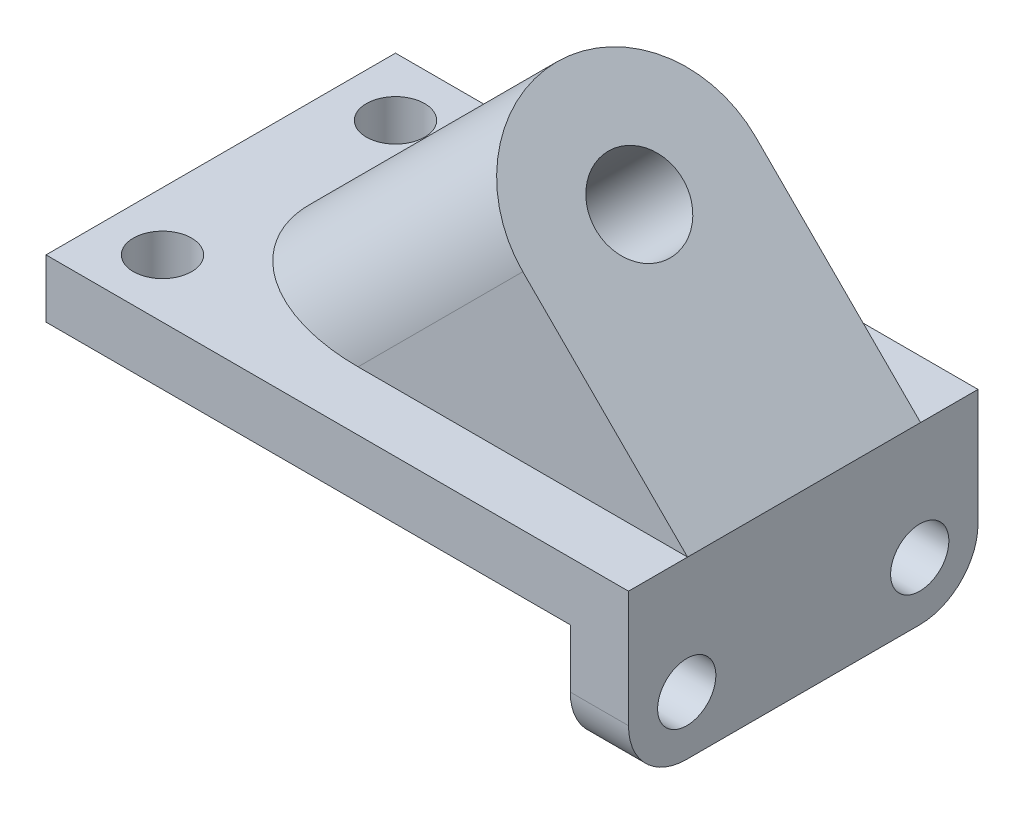
SolidWorks part; units mm, degrees
ref_plane "Front Plane" through (0, 0, 0) normal (0, 0, 1) x (1, 0, 0)
ref_plane "Top Plane" through (0, 0, 0) normal (0, 1, 0) x (1, 0, 0)
ref_plane "Right Plane" through (0, 0, 0) normal (1, 0, 0) x (0, 0, -1)
sketch "Sketch1" plane through (0, 0, 0) normal (0, 1, 0) x (1, 0, 0)
  line L0 (0, 0) -> (127, 0)
  line L1 (127, 0) -> (127, 76.2)
  line L2 (127, 76.2) -> (0, 76.2)
  line L3 (0, 76.2) -> (0, 0)
extrude "Boss-Extrude1" add sketch "Sketch1" along normal blind 12.7
sketch "Sketch2" plane through (0, 12.7, 0) normal (0, 1, 0) x (1, 0, 0)
  line L0 (0, 0) -> (127, 0) construction
  line L1 (127, 76.2) -> (114.3, 76.2)
  line L2 (127, 76.2) -> (127, 0)
  line L3 (127, 0) -> (114.3, 0)
  line L4 (114.3, 76.2) -> (114.3, 0)
extrude "Boss-Extrude2" add sketch "Sketch2" against normal blind 38.1
sketch "Sketch5" plane through (0, 12.7, 0) normal (0, 1, 0) x (1, 0, 0)
  circle A0 centre (12.7, 63.5) radius 6.35
  circle A1 centre (12.7, 12.7) radius 6.35
  dimension "D1" = 12.7
fillet "Fillet1" radius 12.7 1 edges at (120.65, -25.4, 0)
fillet "Fillet2" radius 12.7 1 edges at (120.65, -25.4, -76.2)
ref_plane "Plane1" through (69.85, 69.85, 0) normal (0.7071, 0.7071, 0) x (0, 0, -1)
sketch "Sketch7" plane through (69.85, 69.85, 0) normal (0.7071, 0.7071, 0) x (0, 0, -1)
  line L0 (63.6781, -80.8223) -> (12.8781, -80.8223)
  line L1 (0, -80.8223) -> (76.2, -80.8223) construction
  line L2 (12.8781, -80.8223) -> (12.8781, -30.0223)
  line L3 (63.6781, -80.8223) -> (63.6781, -30.0223)
  arc A0 (12.8781, -30.0223) -> (63.6781, -30.0223) centre (38.2781, -30.0223) cw
  circle A1 centre (38.2781, -30.0223) radius 9.525
  dimension "D4" = 19.05
  dimension "D1" = 50.8
  dimension "D2" = 50.8
  dimension "D3" = 12.5219
extrude "Boss-Extrude3" add sketch "Sketch7" against normal up to surface up to face at (63.5, 12.7, -38.1)
extrude "Cut-Extrude1" cut sketch "Sketch5" against normal blind 38.1
sketch "Sketch8" plane through (127, 0, 0) normal (1, 0, 0) x (0, 0, -1)
  circle A0 centre (12.7, -12.7) radius 6.35
  circle A1 centre (63.5, -12.7) radius 6.35
extrude "Cut-Extrude2" cut sketch "Sketch8" against normal blind 38.1
